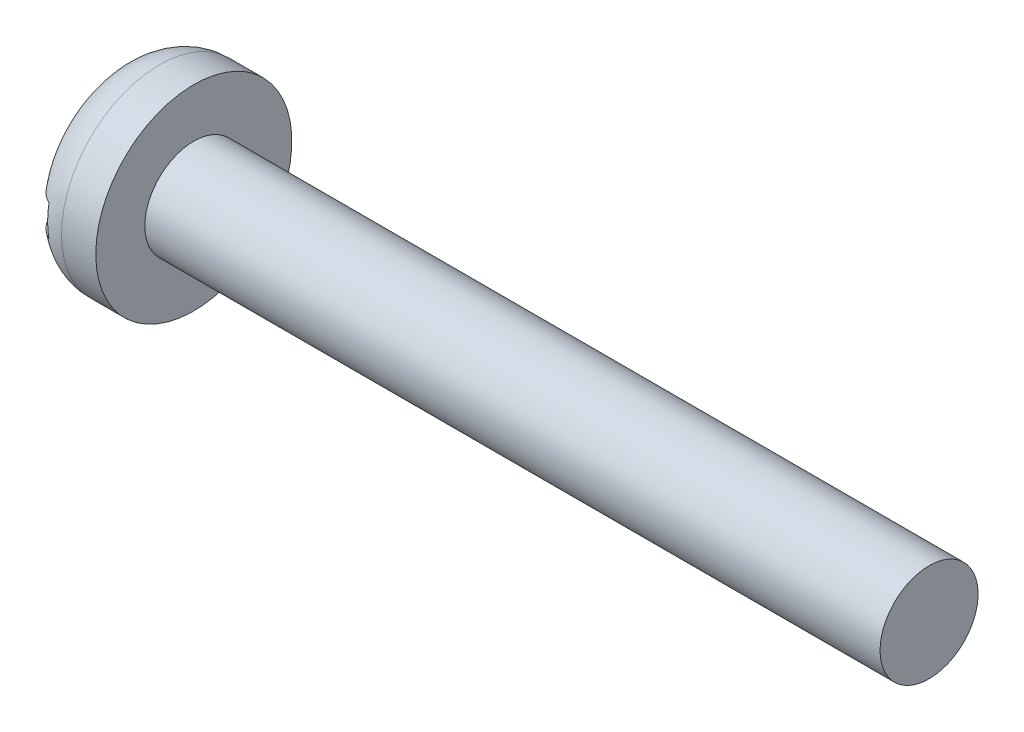
SolidWorks part; units mm, degrees
ref_plane "Plane1" through (0, 0, 0) normal (0, 0, 1) x (1, 0, 0)
ref_plane "Plane2" through (0, 0, 0) normal (0, 1, 0) x (1, 0, 0)
ref_plane "Plane3" through (0, 0, 0) normal (1, 0, 0) x (0, 0, -1)
sketch "BodySke" plane through (0, 0, 0) normal (0, 0, 1) x (1, 0, 0)
  line L0 (4.6, 3) -> (4.6, 6)
  line L1 (0, 0) -> (0, 3.5)
  line L2 (-25.4, 0) -> (127, 0) construction
  line L3 (49.6, 0) -> (0, 0)
  line L4 (4.6, 3) -> (49.6, 3)
  line L5 (49.6, 3) -> (49.6, 0)
  line L6 (2.5, 6) -> (4.6, 6)
  line L7 (4.6, -3) -> (49.6, -3) construction
  line L8 (0, -6) -> (4.6, -6) construction
  line L9 (5.6, 4.5875) -> (5.6, -4.9375) construction
  line L10 (-0.4, 6.35) -> (-0.4, -3.175) construction
  arc A0 (0, 3.5) -> (2.5, 6) centre (2.5, 3.5) cw
  point P15 (0, 6)
  dimension "Head_fillet_rad" = 2.5
  dimension "Diameter" = 6
  dimension "Length" = 45
  dimension "Head_ht" = 4.6
  dimension "Head_dia" = 12
  dimension "Advance" = 1
revolve "Base-Revolve" add sketch "BodySke" angle 360 about L2
cosmetic thread "ThreadCosmetic" [suppressed] parameters "Thread_length"=44, "Thread_minor"=4.891
sketch "Sketch2" plane through (0, 0, 0) normal (1, 0, 0) x (0, 0, -1)
  line L0 (6, -0.95) -> (-6, -0.95)
  line L1 (6, -0.95) -> (6, 0.95)
  line L2 (-6, 0.95) -> (6, 0.95)
  line L3 (-6, 0.95) -> (-6, -0.95)
  dimension "D1" = 12
  dimension "Slot_width" = 1.9
  dimension "D2" = 6
  dimension "D3" = 0.95
extrude "Slot" cut sketch "Sketch2" along normal blind 1.4
sketch "ThdSchSke" plane through (0, 0, 0) normal (0, 0, 1) x (1, 0, 0)
  line L0 (5.6, -2.4455) -> (5.2117, -3)
  line L1 (5.6, -2.4455) -> (5.9883, -3)
  line L2 (5.9883, -3) -> (5.9883, -3.75)
  line L3 (-3.175, 0) -> (5.1513, 0) construction
  line L5 (5.9883, -3.75) -> (5.2117, -3.75)
  line L6 (5.2117, -3.75) -> (5.2117, -3)
  dimension "Diameter" = 6
  dimension "SideAngle" = 55
  dimension "VeeAngle" = 70
  dimension "Thread_minor" = 4.891
  dimension "Overcut" = 7.5
  dimension "Start" = 5.6
revolve "ThreadSchematic" [suppressed] cut sketch "ThdSchSke" angle 360 about L3
pattern_linear "ThdSchPat" [suppressed]
equation "\"D1@Sketch2\" = \"Head_dia@BodySke\""
equation "\"D2@Sketch2\" = \"D1@Sketch2\" / 2"
equation "\"D3@Sketch2\" = \"Slot_width@Sketch2\" / 2"
equation "\"Thread_length@ThreadCosmetic\" = ((sgn( (\"Length@BodySke\" - \"Advance@BodySke\" ) - \"Thread_nom@BodySke\" )-1)*( (\"Length@BodySke\" - \"Advance@BodySke\" ) - \"Thread_nom@BodySke\" ))/-2+ \"Thread_nom@BodySke\""
equation "\"Thread_minor@ThdSchSke\" = \"Thread_minor@ThreadCosmetic\""
equation "\"Diameter@ThdSchSke\" = \"Diameter@BodySke\""
equation "\"Overcut@ThdSchSke\" = \"Diameter@BodySke\" * 1.25"
equation "\"Start@ThdSchSke\" = \"Head_ht@BodySke\" + \"Length@BodySke\" - \"Thread_length@ThreadCosmetic\"  '---Non-countersunk---"
equation "\"Num_threads@ThdSchPat\" = int( \"Thread_length@ThreadCosmetic\" / \"Advance@BodySke\" + 0.999 )  + 1"
equation "\"Advance@ThdSchPat\" = \"Thread_length@ThreadCosmetic\" /  (\"Num_threads@ThdSchPat\" - 1) 'relax it"
